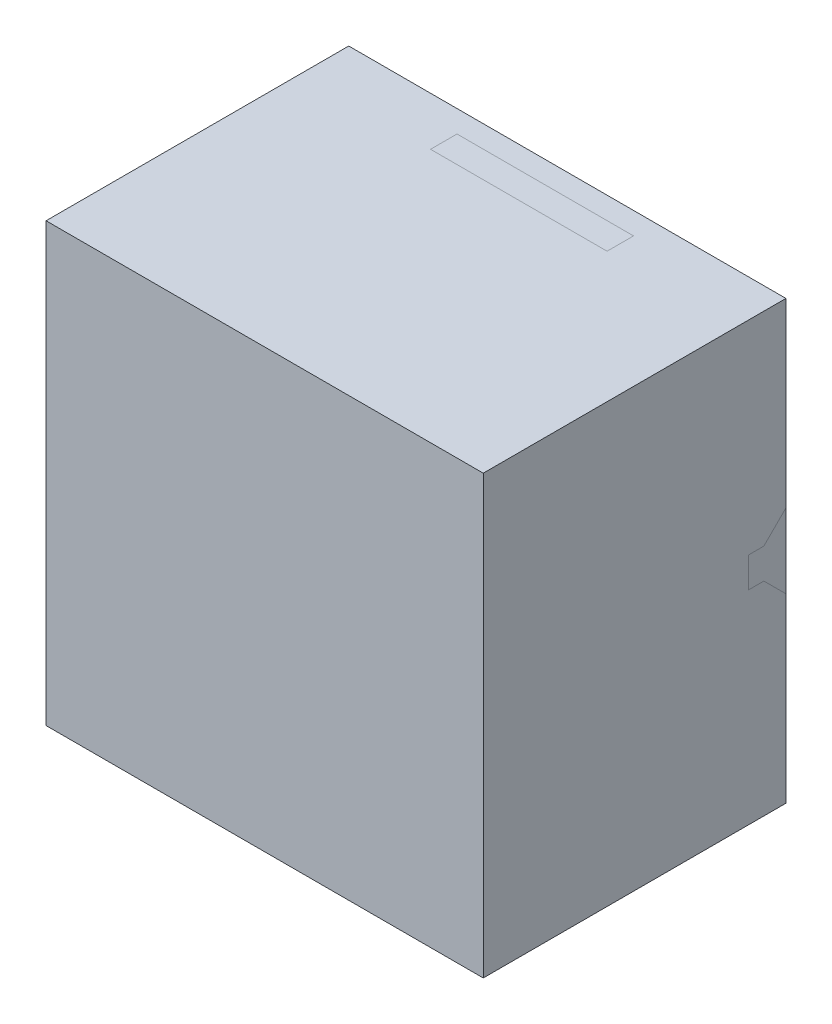
SolidWorks part; units mm, degrees
other "DetailItem1"
other "DetailItem2"
other "DetailItem3"
other "DetailItem4"
other "DetailItem5" parameters "RD1"=99.06, "RD2"=68.58, "RD3"=99.06
ref_plane "Front Plane" through (0, 0, 0) normal (0, 0, 1) x (1, 0, 0)
ref_plane "Top Plane" through (0, 0, 0) normal (0, 1, 0) x (1, 0, 0)
ref_plane "Right Plane" through (0, 0, 0) normal (1, 0, 0) x (0, 0, -1)
sketch "Sketch1" plane through (0, 0, 0) normal (0, 0, 1) x (1, 0, 0)
  line L1 (-49.53, 49.53) -> (49.53, 49.53)
  line L2 (-49.53, 49.53) -> (-49.53, -49.53)
  line L3 (-49.53, -49.53) -> (49.53, -49.53)
  line L4 (49.53, 49.53) -> (49.53, -49.53)
  line L5 (-49.53, 49.53) -> (49.53, -49.53) construction
  line L6 (-49.53, -49.53) -> (49.53, 49.53) construction
  point P0 (0, 0)
  dimension "D1" = 99.06
extrude "Boss-Extrude1" add sketch "Sketch1" along normal blind 68.58
sketch "IO Image"
sketch "Rear IO Sketch" plane through (-49.53, 0, 0) normal (-1, 0, 0) x (0, 0, 1)
  line L0 (0, 0) -> (68.58, 0) construction
  line L1 (65.405, 34.29) -> (59.055, 34.29)
  line L2 (65.405, 34.29) -> (65.405, -34.29)
  line L3 (65.405, -34.29) -> (59.055, -34.29)
  line L4 (59.055, 34.29) -> (59.055, -34.29)
  line L5 (65.405, 34.29) -> (59.055, -34.29) construction
  line L6 (65.405, -34.29) -> (59.055, 34.29) construction
  line L7 (0, 49.53) -> (0, -49.53) construction
  line L8 (68.58, 49.53) -> (68.58, -49.53) construction
  line L9 (48.0947, 30.6513) -> (26.1488, 30.6513) construction
  line L10 (22.9738, 34.0803) -> (51.5237, 34.0803)
  line L11 (22.9738, 34.0803) -> (22.9738, -12.2747)
  line L12 (22.9738, -12.2747) -> (51.5237, -12.2747)
  line L13 (51.5237, 34.0803) -> (51.5237, -12.2747)
  line L14 (48.0947, -8.8467) -> (26.1488, -8.8467) construction
  line L15 (48.0947, 30.6513) -> (48.0947, -8.8467) construction
  line L16 (52.1482, -16.6526) -> (40.7551, -16.6526) construction
  line L17 (26.1488, 30.6513) -> (26.1488, -8.8467) construction
  line L18 (40.7551, -16.6526) -> (40.7551, -31.6915) construction
  line L19 (52.1482, -31.6915) -> (40.7551, -31.6915) construction
  line L20 (52.1482, -16.6526) -> (52.1482, -31.6915) construction
  line L21 (53.7357, -15.0651) -> (53.7357, -33.279)
  line L22 (53.7357, -33.279) -> (39.1676, -33.279)
  line L23 (39.1676, -15.0651) -> (39.1676, -33.279)
  line L24 (53.7357, -15.0651) -> (39.1676, -15.0651)
  line L25 (39.1676, -15.0651) -> (22.9738, -15.0651) construction
  line L26 (18.1445, 37.9965) -> (10.6685, 37.9965) construction
  line L27 (18.1445, -38.0636) -> (10.6685, -38.0636) construction
  line L28 (18.1445, 37.9965) -> (18.1445, -38.0636) construction
  line L29 (10.6685, 37.9965) -> (10.6685, -38.0636) construction
  line L30 (19.732, 39.584) -> (19.732, -39.6511)
  line L31 (19.732, -39.6511) -> (9.081, -39.6511)
  line L32 (9.081, 39.584) -> (9.081, -39.6511)
  line L33 (19.732, 39.584) -> (9.081, 39.584)
  circle A1 centre (31.3953, -21.9834) radius 6.9183
  point P0 (62.23, 0)
  point P26 (31.3953, -21.9834)
  point P36 (68.58, 0)
  point P38 (19.0888, -38.0636)
  point P39 (21.1454, 37.9965)
  dimension "D10" = 1.5875
  dimension "D1" = 6.35
  dimension "D2" = 3.175
  dimension "D3" = 34.29
  dimension "D4" = 46.355
  dimension "D5" = 3.175
  dimension "D6" = 3.429
  dimension "D7" = 3.428
  dimension "D8" = 3.429
  dimension "D9" = 1.5875
sketch "Left IO Sketch" plane through (0, 49.53, 0) normal (0, 1, 0) x (1, 0, 0)
  line L0 (0, 0) -> (0, -68.58) construction
  line L1 (49.53, -68.58) -> (-49.53, -68.58) construction
  line L2 (49.53, 0) -> (-49.53, 0) construction
  line L3 (20, -5) -> (-20, -5)
  line L4 (20, -5) -> (20, -11)
  line L5 (20, -11) -> (-20, -11)
  line L6 (-20, -5) -> (-20, -11)
  line L7 (20, -5) -> (-20, -11) construction
  line L8 (20, -11) -> (-20, -5) construction
  point P5 (0, -8)
  dimension "D1" = 6
  dimension "D2" = 5
  dimension "D3" = 20
sketch "Front IO Sketch" plane through (49.53, 0, 0) normal (1, 0, 0) x (0, 0, -1)
  line L0 (0, 0) -> (-68.58, 0) construction
  line L1 (-68.58, -49.53) -> (-68.58, 49.53) construction
  line L2 (0, -49.53) -> (0, 49.53) construction
  line L3 (-8.429, -3.429) -> (-5, -3.429)
  line L4 (-8.429, -3.429) -> (-8.429, 3.429)
  line L5 (-8.429, 3.429) -> (-5, 3.429)
  line L6 (-5, -3.429) -> (-5, 3.429) construction
  line L7 (-8.429, -3.429) -> (-5, 3.429) construction
  line L8 (-8.429, 3.429) -> (-5, -3.429) construction
  line L9 (-5, 3.429) -> (0, 8.429)
  line L10 (-5, -3.429) -> (0, -8.429)
  line L11 (0, -8.429) -> (0, 8.429)
  point P5 (-6.7145, 0)
  dimension "D1" = 3.429
  dimension "D2" = 3.429
  dimension "D3" = 5
  dimension "D4" = 135
split line "Rear IO Split"
split line "Left IO Split"
split line "Front IO Split"
